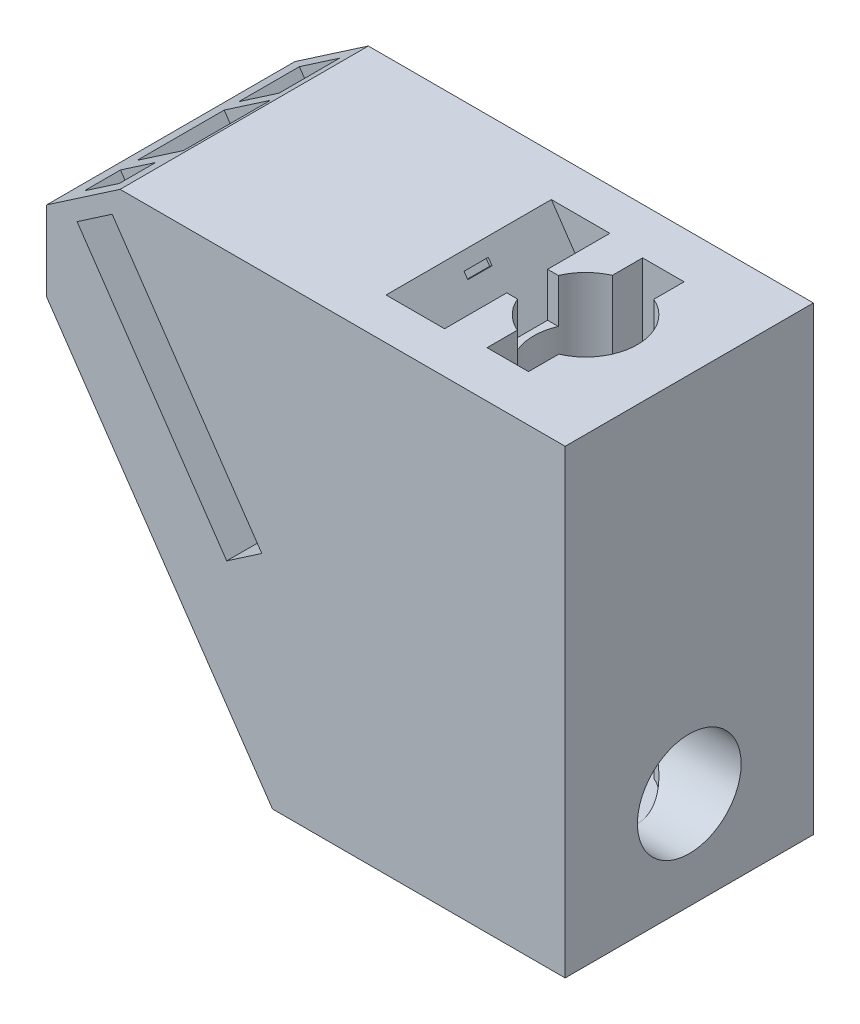
SolidWorks part; units mm, degrees
ref_plane "Front Plane" through (0, 0, 0) normal (0, 0, 1) x (1, 0, 0)
ref_plane "Top Plane" through (0, 0, 0) normal (0, 1, 0) x (1, 0, 0)
ref_plane "Right Plane" through (0, 0, 0) normal (1, 0, 0) x (0, 0, -1)
sketch "Sketch1" plane through (0, 0, 0) normal (0, 0, 1) x (1, 0, 0)
  line L6 (2.54, 23.749) -> (2.54, 14.224) construction
  line L7 (0, 0) -> (5.08, 0)
  line L8 (0, 0) -> (0, 14.224)
  line L9 (0, 14.224) -> (5.08, 14.224)
  line L14 (5.08, 0) -> (5.08, 14.224)
  line L19 (-4.6156, 24.384) -> (-4.0424, 23.5451)
  line L29 (-11.679, 6.821) -> (-21.27, 20.8572)
  line L31 (-22.86, -3.81) -> (8.89, -3.81)
  line L33 (-3.4692, 22.7063) -> (-1.0331, 19.1411)
  line L34 (-21.27, 20.8572) -> (-22.86, 19.7707)
  line L35 (-4.0424, 23.5451) -> (-3.4692, 22.7063)
  line L36 (-28.3165, 23.749) -> (25.4257, 23.749)
  line L37 (-28.3165, 23.749) -> (-28.3165, 38.989)
  line L38 (-28.3165, 38.989) -> (25.4257, 38.989)
  line L39 (25.4257, 23.749) -> (25.4257, 38.989)
  line L40 (2.54, 38.989) -> (2.54, 23.749) construction
  line L41 (2.54, 31.369) -> (-11.8891, 14.2184) construction
  line L42 (-21.27, 20.8572) -> (-17.9673, 23.1139)
  line L43 (-11.679, 6.821) -> (-8.3764, 9.0777)
  line L44 (-8.3764, 9.0777) -> (-9.5047, 10.729)
  line L45 (-1.0331, 19.1411) -> (0, 19.1411)
  line L46 (-17.9673, 23.1139) -> (-16.1085, 24.384)
  line L47 (-16.1085, 24.384) -> (-4.6156, 24.384)
  line L48 (0, 19.1411) -> (0, 14.224)
  line L49 (-4.329, 23.9646) -> (-17.443, 23.4721)
  line L50 (-4.329, 23.9646) -> (-3.7558, 23.1257)
  line L51 (-3.7558, 23.1257) -> (-8.3764, 9.0777)
  line L52 (-8.8063, 9.7068) -> (2.54, 42.6656) construction
  line L53 (2.54, 38.989) -> (2.54, 42.6656) construction
  line L54 (8.89, -3.81) -> (8.89, 24.384)
  line L55 (8.89, 24.384) -> (5.08, 24.384)
  line L56 (5.08, 14.224) -> (5.08, 24.384)
  line L57 (2.54, 23.749) -> (-4.0424, 23.5451) construction
  line L58 (2.54, 38.989) -> (-4.0424, 23.5451) construction
  line L59 (-4.0424, 23.5451) -> (-9.5047, 10.729) construction
  line L60 (-4.0424, 23.5451) -> (-17.9673, 23.1139) construction
  line L61 (-17.9673, 23.1139) -> (-9.5047, 10.729)
  line L62 (-8.8063, 9.7068) -> (-9.8549, 8.9903) construction
  line L63 (-9.8549, 8.9903) -> (-18.2379, 21.2588) construction
  line L64 (-18.2379, 21.2588) -> (-17.1893, 21.9753) construction
  line L69 (-17.1893, 21.9753) -> (2.54, 24.3311) construction
  line L70 (-22.86, 19.7707) -> (-22.86, -3.81)
  dimension "D1" = 5.08
  dimension "D2" = 14.224
  dimension "D3" = 0.635
  dimension "D4" = 10.16
  dimension "D5" = 4
  dimension "D6" = 15.24
  dimension "D7" = 17
  dimension "D8" = 31.75
  dimension "D9" = 1.59
  dimension "D10" = 1.016
  dimension "D11" = 6.35
  dimension "D12" = 3.81
  dimension "D13" = 3.81
  dimension "D14" = 0.635
  dimension "D15" = 0.508
  dimension "D16" = 0.508
  dimension "D17" = 0.762
  dimension "D18" = 14.859
  dimension "D19" = 1.27
  dimension "D20" = 15
extrude "Boss-Extrude1" add sketch "Sketch1" along normal blind 2.5 contours L34 L70 L31 L54 L36 L56 L14 L7 L8 L48 L45 L33 L35 L19 L46 L61 L44 L43 L29 | L47 L46 L36 L19 | L56 L36 L54 L55
sketch "Sketch2" plane through (0, 0, 2.5) normal (0, 0, 1) x (1, 0, 0)
  line L0 (-21.27, 20.8572) -> (-11.679, 6.821)
  line L1 (-21.27, 20.8572) -> (-18.0093, 23.0852)
  line L2 (-11.679, 6.821) -> (-8.4184, 9.049)
  line L3 (-18.0093, 23.0852) -> (-8.4184, 9.049)
  line L4 (-18.0093, 23.0852) -> (-16.1085, 24.384)
  line L5 (-16.1085, 24.384) -> (8.89, 24.384)
  line L6 (8.89, 24.384) -> (8.89, -3.81)
  line L7 (8.89, -3.81) -> (-22.86, -3.81)
  line L8 (-22.86, -3.81) -> (-22.86, 19.7707)
  line L9 (-22.86, 19.7707) -> (-21.27, 20.8572)
  line M1 (-21.27, 20.8572) -> (-22.86, 19.7707)
  line M2 (-22.86, 19.7707) -> (-22.86, -3.81)
  line M3 (-22.86, -3.81) -> (8.89, -3.81)
  line M4 (8.89, -3.81) -> (8.89, 24.384)
  line M5 (8.89, 24.384) -> (5.08, 24.384)
  line M6 (5.08, 24.384) -> (5.08, 0)
  line M7 (5.08, 0) -> (0, 0)
  line M8 (0, 0) -> (0, 19.1411)
  line M9 (0, 19.1411) -> (-1.0331, 19.1411)
  line M10 (-1.0331, 19.1411) -> (-3.7558, 23.1257)
  line M11 (-3.7558, 23.1257) -> (-8.3764, 9.0777)
  line M12 (-8.3764, 9.0777) -> (-11.679, 6.821)
  line M13 (-11.679, 6.821) -> (-21.27, 20.8572)
extrude "Boss-Extrude2" add sketch "Sketch2" along normal blind 6.35 contours M13 M1 M2 M3 M4 M5 M6 M7 M8 M9 M10 M11 M12 | L5 L4 L3 M12 M11 M10 M9 M8 M7 M6
sketch "Sketch3" plane through (0, 0, 0) normal (0, 0, -1) x (-1, 0, 0)
  line L0 (-8.89, 24.384) -> (-8.89, -3.81)
  line L1 (-8.89, -3.81) -> (22.86, -3.81)
  line L2 (22.86, -3.81) -> (22.86, 19.7707)
  line L3 (22.86, 19.7707) -> (21.27, 20.8572)
  line L4 (21.27, 20.8572) -> (11.679, 6.821)
  line L5 (11.679, 6.821) -> (8.3764, 9.0777)
  line L6 (8.3764, 9.0777) -> (18.0093, 23.0852)
  line L7 (18.0093, 23.0852) -> (16.1085, 24.384)
  line L8 (16.1085, 24.384) -> (-8.89, 24.384)
extrude "Boss-Extrude3" add sketch "Sketch3" along normal blind 6.35
sketch "Sketch4" plane through (0, 24.384, 0) normal (0, 1, 0) x (1, 0, 0)
  line L0 (2.54, 0) -> (2.54, -2.5) construction
  line L1 (-4.6156, 0) -> (5.08, 0) construction
  line L2 (5.08, -2.5) -> (-4.6156, -2.5) construction
  line L3 (-22.86, 0) -> (8.89, 0) construction
  line L4 (5.08, -2.5) -> (5.08, 0) construction
  circle A0 centre (2.54, -1.25) radius 3.175
  dimension "D2" = 6.35
  dimension "D1" = 2.54
extrude "Cut-Extrude1" cut sketch "Sketch4" against normal blind 25.4
sketch "Sketch5" plane through (0, -1.016, 0) normal (0, 1, 0) x (1, 0, 0)
  circle A0 centre (2.54, -1.25) radius 1.5875
  circle A1 centre (2.54, -1.25) radius 3.175
  circle A2 centre (2.54, -1.25) radius 3.175 construction
  dimension "D2" = 3.175
  dimension "D1" = 0
extrude "Cut-Extrude2" cut sketch "Sketch5" against normal blind 25.4
sketch "Sketch6" plane through (0, 0, 8.85) normal (0, 0, 1) x (1, 0, 0)
  line L0 (-22.86, 16.4309) -> (-9.0294, -3.81)
  line L1 (-22.86, 19.7707) -> (-22.86, -3.81) construction
  line L2 (-22.86, -3.81) -> (8.89, -3.81) construction
  line L3 (-11.679, 6.821) -> (-21.27, 20.8572) construction
  line L4 (-22.86, 16.4309) -> (-22.86, -3.81)
  line L5 (-22.86, -3.81) -> (-9.0294, -3.81)
  dimension "D1" = 3.81
extrude "Cut-Extrude3" cut sketch "Sketch6" against normal blind 25.4
sketch "Sketch7" plane through (8.89, 0, 0) normal (1, 0, 0) x (0, 0, -1)
  line L0 (1.925, -1.016) -> (-4.425, -1.016) construction
  line L1 (1.925, -1.016) -> (-4.425, -1.016)
  line L2 (-8.85, 2.159) -> (6.35, 2.159) construction
  line L3 (-8.85, -3.81) -> (-8.85, 24.384) construction
  line L4 (6.35, 24.384) -> (6.35, -3.81) construction
  circle A0 centre (-1.25, 2.159) radius 3.175
  dimension "D1" = 6.35
extrude "Cut-Extrude4" cut sketch "Sketch7" against normal up to next contours L2 A0 | A0 L2
sketch "Sketch8" plane through (0, 24.384, 0) normal (0, 1, 0) x (1, 0, 0)
  line L1 (1.27, -6.0125) -> (3.81, -6.0125)
  line L2 (1.27, -6.0125) -> (1.27, 3.5125)
  line L3 (1.27, 3.5125) -> (3.81, 3.5125)
  line L4 (3.81, -6.0125) -> (3.81, 3.5125)
  line L5 (1.27, -6.0125) -> (3.81, 3.5125) construction
  line L6 (1.27, 3.5125) -> (3.81, -6.0125) construction
  point P0 (2.54, -1.25)
  dimension "D1" = 9.525
  dimension "D2" = 2.54
extrude "Cut-Extrude5" cut sketch "Sketch8" against normal up to surface (25.4 mm away) up to face at (2.54, -1.016, 2.8375)
sketch "Sketch9" plane through (-6.8946, 10.0902, 0) normal (-0.5642, 0.8257, 0) x (0.8257, 0.5642, 0)
  line L1 (-1.8455, -4.6028) -> (-3.5726, -4.6028)
  line L2 (-3.5726, -4.6028) -> (-3.5726, -5.6188)
  line L3 (-3.5726, -5.6188) -> (-2.6836, -5.6188)
  line L4 (-2.6836, -5.6188) -> (-2.6836, -8.85)
  line L5 (-1.8455, -8.85) -> (-5.7946, -8.85) construction
  line L6 (-2.6836, -8.85) -> (-1.8455, -8.85)
  line L9 (-1.7946, 6.35) -> (-1.7946, 0) construction
  line L10 (-3.6235, 0.7312) -> (-3.6235, 1.6202)
  line L11 (-1.7946, 0.7312) -> (-3.6235, 0.7312)
  line L12 (-2.7091, 0.7312) -> (-2.7091, -4.6028) construction
  line L13 (-5.7946, 6.35) -> (-5.2866, 6.35)
  line L14 (-5.7946, 6.35) -> (-5.7946, -8.85)
  line L15 (-5.7946, -8.85) -> (-5.2866, -8.85)
  line L16 (-5.2866, 6.35) -> (-5.2866, -8.85)
  line L17 (-0.6688, -2.5) -> (-0.6688, 0) construction
  line L18 (-1.8455, -8.85) -> (-1.8455, -2.5) construction
  line L19 (-3.6235, 1.6202) -> (-2.3026, 1.6202)
  line L20 (-2.3026, 1.6202) -> (-2.3026, 6.35)
  line L21 (-5.7946, 6.35) -> (-1.7946, 6.35) construction
  line L23 (-1.7946, -2.5) -> (-1.7946, 0) construction
  line L24 (-1.7946, 0.7312) -> (-1.7946, 6.35)
  line L27 (-1.8455, 6.35) -> (0.4567, 6.35) construction
  line L28 (-2.3026, 6.35) -> (-1.7946, 6.35)
  point P28 (-0.6688, -1.25)
  line M15 (-1.7946, 0) -> (-1.7946, 6.35)
  line M16 (-1.7946, 6.35) -> (-5.7946, 6.35)
  line M17 (-5.7946, 6.35) -> (-5.7946, -8.85)
  line M18 (-5.7946, -8.85) -> (-1.8455, -8.85)
  line M19 (-1.8455, -8.85) -> (-1.8455, -2.5)
  dimension "D1" = 0.508
  dimension "D2" = 5.334
  dimension "D3" = 1.9812
  dimension "D4" = 0.508
  dimension "D5" = 0.889
  dimension "D6" = 0.889
  dimension "D7" = 1.016
  dimension "D8" = 1.778
extrude "Boss-Extrude4" add sketch "Sketch9" along normal up to surface (17 mm away) contours L16 M16 M17 M18 | L20 L19 L10 L11 M15 M16 | L3 L4 L1 L2 M18 M19 up to face at (-17.2912, 23.5758, 1.25)
sketch "Sketch10" plane through (-6.8946, 10.0902, 0) normal (-0.5642, 0.8257, 0) x (0.8257, 0.5642, 0)
  line L15 (-5.2866, -8.85) -> (-2.6836, -8.85)
  line L16 (-2.6836, -8.85) -> (-2.6836, -5.6188)
  line L17 (-2.6836, -5.6188) -> (-3.5726, -5.6188)
  line L18 (-3.5726, -5.6188) -> (-3.5726, -4.6028)
  line L19 (-3.5726, -4.6028) -> (-1.8455, -4.6028)
  line L20 (-1.8455, -4.6028) -> (-1.8455, -2.5)
  line L21 (-1.8455, -2.5) -> (-1.7946, -2.5)
  line L22 (-1.7946, -2.5) -> (-1.7946, 0)
  line L23 (-1.7946, 0) -> (-1.7946, 0.7312)
  line L24 (-1.7946, 0.7312) -> (-3.6235, 0.7312)
  line L25 (-3.6235, 0.7312) -> (-3.6235, 1.6202)
  line L26 (-3.6235, 1.6202) -> (-2.3026, 1.6202)
  line L27 (-2.3026, 1.6202) -> (-2.3026, 6.35)
  line L28 (-2.3026, 6.35) -> (-5.2866, 6.35)
  line L29 (-5.2866, 6.35) -> (-5.2866, -8.85)
  line L30 (-5.2866, -8.85) -> (-2.6836, -8.85)
  line L31 (-2.6836, -8.85) -> (-2.6836, -5.6188)
  line L32 (-2.6836, -5.6188) -> (-3.5726, -5.6188)
  line L33 (-3.5726, -5.6188) -> (-3.5726, -4.6028)
  line L34 (-3.5726, -4.6028) -> (-1.8455, -4.6028)
  line L35 (-1.8455, -4.6028) -> (-1.8455, -2.5)
  line L36 (-1.8455, -2.5) -> (-1.7946, -2.5)
  line L37 (-1.7946, -2.5) -> (-1.7946, 0)
  line L38 (-1.7946, 0) -> (-1.7946, 0.7312)
  line L39 (-1.7946, 0.7312) -> (-3.6235, 0.7312)
  line L40 (-3.6235, 0.7312) -> (-3.6235, 1.6202)
  line L41 (-3.6235, 1.6202) -> (-2.3026, 1.6202)
  line L42 (-2.3026, 1.6202) -> (-2.3026, 6.35)
  line L43 (-2.3026, 6.35) -> (-5.2866, 6.35)
  line L44 (-5.2866, 6.35) -> (-5.2866, -8.85)
  dimension "D1" = 0
extrude "Boss-Extrude5" add sketch "Sketch10" along normal blind 1.016
sketch "Sketch11" plane through (-16.4856, 24.1263, 0) normal (-0.5642, 0.8257, 0) x (0.8257, 0.5642, 0)
  line L0 (-7.7204, -8.85) -> (-5.2866, -8.85) construction
  line L1 (-5.2866, -8.85) -> (-5.2866, 6.35) construction
  line L2 (-5.2866, 6.35) -> (-7.7204, 6.35) construction
  line L3 (-7.7204, 6.35) -> (-7.7204, -8.85) construction
  line L4 (-3.6235, 0.7312) -> (-1.8455, 0.7312) construction
  line L5 (-1.8455, 0.7312) -> (-1.8455, 0) construction
  line L6 (-1.8455, 0) -> (-0.6688, 0) construction
  line L7 (-0.6688, 0) -> (-0.6688, -2.5) construction
  line L8 (-0.6688, -2.5) -> (-1.8455, -2.5) construction
  line L9 (-1.8455, -2.5) -> (-1.8455, -4.6028) construction
  line L10 (-1.8455, -4.6028) -> (-3.5726, -4.6028) construction
  line L11 (-3.5726, -4.6028) -> (-3.5726, -5.6188) construction
  line L12 (-3.5726, -5.6188) -> (-2.6836, -5.6188) construction
  line L13 (-2.6836, -5.6188) -> (-2.6836, -8.85) construction
  line L14 (-2.6836, -8.85) -> (0.4567, -8.85) construction
  line L15 (0.4567, -8.85) -> (0.4567, 6.35) construction
  line L16 (0.4567, 6.35) -> (-2.3026, 6.35) construction
  line L17 (-2.3026, 6.35) -> (-2.3026, 1.6202) construction
  line L18 (-2.3026, 1.6202) -> (-3.6235, 1.6202) construction
  line L19 (-3.6235, 1.6202) -> (-3.6235, 0.7312) construction
  line L20 (-7.7204, -8.85) -> (-5.2866, -8.85)
  line L21 (-5.2866, -8.85) -> (-5.2866, 6.35)
  line L22 (-5.2866, 6.35) -> (-7.7204, 6.35)
  line L23 (-7.7204, 6.35) -> (-7.7204, -8.85)
  line L24 (-3.6235, 0.7312) -> (-1.8455, 0.7312)
  line L25 (-1.8455, 0.7312) -> (-1.8455, 0)
  line L26 (-1.8455, 0) -> (-0.6688, 0)
  line L27 (-0.6688, 0) -> (-0.6688, -2.5)
  line L28 (-0.6688, -2.5) -> (-1.8455, -2.5)
  line L29 (-1.8455, -2.5) -> (-1.8455, -4.6028)
  line L30 (-1.8455, -4.6028) -> (-3.5726, -4.6028)
  line L31 (-3.5726, -4.6028) -> (-3.5726, -5.6188)
  line L32 (-3.5726, -5.6188) -> (-2.6836, -5.6188)
  line L33 (-2.6836, -5.6188) -> (-2.6836, -8.85)
  line L34 (-2.6836, -8.85) -> (0.4567, -8.85)
  line L35 (0.4567, -8.85) -> (0.4567, 6.35)
  line L36 (0.4567, 6.35) -> (-2.3026, 6.35)
  line L37 (-2.3026, 6.35) -> (-2.3026, 1.6202)
  line L38 (-2.3026, 1.6202) -> (-3.6235, 1.6202)
  line L39 (-3.6235, 1.6202) -> (-3.6235, 0.7312)
  line L41 (-1.8455, 0) -> (-0.6688, 0)
  line L42 (-1.8455, 0) -> (-1.8455, -2.5)
  line L43 (-1.8455, -2.5) -> (-0.6688, -2.5)
  line L44 (-0.6688, 0) -> (-0.6688, -2.5)
  line M25 (-3.6235, 0.7312) -> (-1.8455, 0.7312)
  line M26 (-1.8455, 0.7312) -> (-1.8455, 0)
  line M27 (-1.8455, 0) -> (-0.6688, 0)
  line M28 (-0.6688, 0) -> (-0.6688, -2.5)
  line M29 (-0.6688, -2.5) -> (-1.8455, -2.5)
  line M30 (-1.8455, -2.5) -> (-1.8455, -4.6028)
  line M31 (-1.8455, -4.6028) -> (-3.5726, -4.6028)
  line M32 (-3.5726, -4.6028) -> (-3.5726, -5.6188)
  line M33 (-3.5726, -5.6188) -> (-2.6836, -5.6188)
  line M34 (-2.6836, -5.6188) -> (-2.6836, -8.85)
  line M35 (-2.6836, -8.85) -> (0.4567, -8.85)
  line M36 (0.4567, -8.85) -> (0.4567, 6.35)
  line M37 (0.4567, 6.35) -> (-2.3026, 6.35)
  line M38 (-2.3026, 6.35) -> (-2.3026, 1.6202)
  line M39 (-2.3026, 1.6202) -> (-3.6235, 1.6202)
  line M40 (-3.6235, 1.6202) -> (-3.6235, 0.7312)
extrude "Boss-Extrude6" add sketch "Sketch11" along normal blind 1.27 contours L42 M27 M29 M28 | M40 M25 M26 M27 M28 M29 M30 M31 M32 M33 M34 M35 M36 M37 M38 M39 | L22 L23 L20 L21
sketch "Sketch12" plane through (0, 0, 8.85) normal (0, 0, 1) x (1, 0, 0)
  line L0 (-16.1085, 24.384) -> (-18.3596, 24.384)
  line L1 (-19.4178, 23.6609) -> (-16.825, 25.4326) construction
  line L2 (-18.3596, 24.384) -> (-16.825, 25.4326)
  line L3 (-16.825, 25.4326) -> (-16.1085, 24.384)
  line L4 (-22.86, 19.7707) -> (-22.86, 21.3089)
  line L5 (-23.5765, 20.8193) -> (-21.567, 22.1923) construction
  line L6 (-22.86, 21.3089) -> (-23.5765, 20.8193)
  line L7 (-23.5765, 20.8193) -> (-22.86, 19.7707)
extrude "Cut-Extrude6" cut sketch "Sketch12" against normal through all
sketch "Sketch13" plane through (0, 19.1411, 0) normal (0, 1, 0) x (1, 0, 0)
  line L3 (-0.3786, 0) -> (-1.0331, 0)
  line L4 (-1.0331, 0) -> (-1.0331, -2.5)
  line L5 (-1.0331, -2.5) -> (-0.3786, -2.5)
  line L6 (-0.3786, 0) -> (-1.0331, 0)
  line L7 (-1.0331, 0) -> (-1.0331, -2.5)
  line L8 (-1.0331, -2.5) -> (-0.3786, -2.5)
  arc A1 (-0.3786, 0) -> (-0.3786, -2.5) centre (2.54, -1.25) ccw
  arc A2 (-0.3786, 0) -> (-0.3786, -2.5) centre (2.54, -1.25) ccw
  dimension "D1" = 0
extrude "Boss-Extrude7" add sketch "Sketch13" along normal blind 2.54
sketch "Sketch14" plane through (8.2119, 5.6112, 0) normal (0.8257, 0.5642, 0) x (0, 0, -1)
  line L0 (0, 22.2288) -> (0, 22.7368) construction
  line L1 (0, 22.7368) -> (-2.5, 22.7368) construction
  line L2 (-2.5, 22.7368) -> (-2.5, 22.2288) construction
  line L3 (-2.5, 22.2288) -> (0, 22.2288) construction
  line L4 (0, 16.3868) -> (0, 21.2128) construction
  line L5 (0, 21.2128) -> (-2.5, 21.2128) construction
  line L6 (-2.5, 21.2128) -> (-2.5, 16.3868) construction
  line L7 (-2.5, 16.3868) -> (0, 16.3868) construction
  line L8 (0, 22.2288) -> (0, 22.7368)
  line L9 (0, 22.7368) -> (-2.5, 22.7368)
  line L10 (-2.5, 22.7368) -> (-2.5, 22.2288)
  line L11 (-2.5, 22.2288) -> (0, 22.2288)
  line L12 (0, 16.3868) -> (0, 21.2128)
  line L13 (0, 21.2128) -> (-2.5, 21.2128)
  line L14 (-2.5, 21.2128) -> (-2.5, 16.3868)
  line L15 (-2.5, 16.3868) -> (0, 16.3868)
  dimension "D1" = 2.5
sketch "Sketch15" plane through (0, 0, 0) normal (0, 0, 1) x (1, 0, 0)
  line L0 (-4.329, 23.9646) -> (-3.7558, 23.1257)
  line L1 (-4.329, 23.9646) -> (-4.6156, 24.384) construction
  line L2 (-3.7558, 23.1257) -> (-1.0331, 19.1411) construction
  line L3 (-4.0745, 23.277) -> (-3.9277, 23.3774)
  line L4 (-4.3038, 23.6126) -> (-4.5389, 23.9567)
  line L5 (-4.5389, 23.9567) -> (-4.329, 23.9646)
  line L6 (-4.3038, 23.6126) -> (-4.157, 23.7129)
  line L7 (-4.0745, 23.277) -> (-3.8257, 22.913)
  line L8 (-3.8257, 22.913) -> (-3.7558, 23.1257)
  line L9 (-4.0424, 23.5451) -> (-3.9209, 23.3673) construction
  line L10 (-4.0424, 23.5451) -> (-4.1638, 23.7229) construction
  line L11 (-1.0331, 19.1411) -> (-3.7558, 23.1257) construction
  line L25 (-1.0331, 19.1411) -> (-1.0331, 21.6811)
  line L26 (-1.0331, 21.6811) -> (-0.3786, 21.6811)
  line L27 (-0.3786, 21.6811) -> (-0.3786, 24.384)
  line L28 (-0.3786, 24.384) -> (-4.6156, 24.384)
  line L29 (-4.6156, 24.384) -> (-4.329, 23.9646)
  line L30 (-4.329, 23.9646) -> (-10.0694, 23.749)
  line L31 (-10.0694, 23.749) -> (-17.0378, 23.749)
  line L32 (-17.0378, 23.749) -> (-18.0093, 23.0852)
  line L33 (-18.0093, 23.0852) -> (-8.9521, 9.9148)
  line L34 (-8.9521, 9.9148) -> (-8.9496, 9.9166)
  line L35 (-8.9496, 9.9166) -> (-8.3764, 9.0777)
  line L36 (-8.3764, 9.0777) -> (-3.7558, 23.1257)
  line L37 (-3.7558, 23.1257) -> (-1.0331, 19.1411)
  line L38 (-1.0331, 19.1411) -> (-1.0331, 21.6811)
  line L39 (-1.0331, 21.6811) -> (-0.3786, 21.6811)
  line L40 (-0.3786, 21.6811) -> (-0.3786, 24.384)
  line L41 (-0.3786, 24.384) -> (-4.6156, 24.384)
  line L42 (-4.6156, 24.384) -> (-4.329, 23.9646)
  line L43 (-4.329, 23.9646) -> (-10.0694, 23.749)
  line L44 (-10.0694, 23.749) -> (-17.0378, 23.749)
  line L45 (-17.0378, 23.749) -> (-18.0093, 23.0852)
  line L46 (-18.0093, 23.0852) -> (-8.9521, 9.9148)
  line L47 (-8.9521, 9.9148) -> (-8.9496, 9.9166)
  line L48 (-8.9496, 9.9166) -> (-8.3764, 9.0777)
  line L49 (-8.3764, 9.0777) -> (-3.7558, 23.1257)
  line L50 (-3.7558, 23.1257) -> (-1.0331, 19.1411)
  line M26 (-4.329, 23.9646) -> (-10.0694, 23.749)
  line M32 (-8.3764, 9.0777) -> (-3.7558, 23.1257)
  dimension "D1" = 0.4064
  dimension "D2" = 0.1778
  dimension "D3" = 0
  dimension "D4" = 0.2032
extrude "Boss-Extrude8" add sketch "Sketch15" along normal blind 2.54 contours L4 L6 L0 M26 | L3 L7 L0 M32
sketch "Sketch16" plane through (0, 0, 0) normal (0, 0, 1) x (1, 0, 0)
  line L0 (-4.157, 23.7129) -> (-3.9277, 23.3774)
  line L1 (-4.0745, 23.277) -> (-3.9277, 23.3774)
  line L2 (-4.0745, 23.277) -> (-4.3038, 23.6126)
  line L3 (-4.3038, 23.6126) -> (-4.157, 23.7129)
  line L17 (-3.8257, 22.913) -> (-4.0745, 23.277)
  line L18 (-4.0745, 23.277) -> (-3.9277, 23.3774)
  line L19 (-3.9277, 23.3774) -> (-1.0331, 19.1411)
  line L20 (-1.0331, 19.1411) -> (-1.0331, 21.6811)
  line L21 (-1.0331, 21.6811) -> (-0.3786, 21.6811)
  line L22 (-0.3786, 21.6811) -> (-0.3786, 24.384)
  line L23 (-0.3786, 24.384) -> (-4.6156, 24.384)
  line L24 (-4.6156, 24.384) -> (-4.157, 23.7129)
  line L25 (-4.157, 23.7129) -> (-4.3038, 23.6126)
  line L26 (-4.3038, 23.6126) -> (-4.5389, 23.9567)
  line L27 (-4.5389, 23.9567) -> (-10.0694, 23.749)
  line L28 (-10.0694, 23.749) -> (-17.0378, 23.749)
  line L29 (-17.0378, 23.749) -> (-18.0093, 23.0852)
  line L30 (-18.0093, 23.0852) -> (-8.9521, 9.9148)
  line L31 (-8.9521, 9.9148) -> (-8.9496, 9.9166)
  line L32 (-8.9496, 9.9166) -> (-8.3764, 9.0777)
  line L33 (-8.3764, 9.0777) -> (-3.8257, 22.913)
  line L34 (-3.8257, 22.913) -> (-4.0745, 23.277)
  line L35 (-4.0745, 23.277) -> (-3.9277, 23.3774)
  line L36 (-3.9277, 23.3774) -> (-1.0331, 19.1411)
  line L37 (-1.0331, 19.1411) -> (-1.0331, 21.6811)
  line L38 (-1.0331, 21.6811) -> (-0.3786, 21.6811)
  line L39 (-0.3786, 21.6811) -> (-0.3786, 24.384)
  line L40 (-0.3786, 24.384) -> (-4.6156, 24.384)
  line L41 (-4.6156, 24.384) -> (-4.157, 23.7129)
  line L42 (-4.157, 23.7129) -> (-4.3038, 23.6126)
  line L43 (-4.3038, 23.6126) -> (-4.5389, 23.9567)
  line L44 (-4.5389, 23.9567) -> (-10.0694, 23.749)
  line L45 (-10.0694, 23.749) -> (-17.0378, 23.749)
  line L46 (-17.0378, 23.749) -> (-18.0093, 23.0852)
  line L47 (-18.0093, 23.0852) -> (-8.9521, 9.9148)
  line L48 (-8.9521, 9.9148) -> (-8.9496, 9.9166)
  line L49 (-8.9496, 9.9166) -> (-8.3764, 9.0777)
  line L50 (-8.3764, 9.0777) -> (-3.8257, 22.913)
  line M19 (-4.0745, 23.277) -> (-3.9277, 23.3774)
  line M26 (-4.157, 23.7129) -> (-4.3038, 23.6126)
  dimension "D1" = 0
extrude "Boss-Extrude9" add sketch "Sketch16" along normal blind 0.508 contours L2 L0 M19 M26
sketch "Sketch17" plane through (0, 0, 2.5) normal (0, 0, -1) x (-1, 0, 0)
  line L0 (4.157, 23.7129) -> (3.9277, 23.3774)
  line L1 (3.9277, 23.3774) -> (4.0745, 23.277)
  line L2 (4.0745, 23.277) -> (4.3038, 23.6126)
  line L3 (4.3038, 23.6126) -> (4.157, 23.7129)
  line L17 (4.0745, 23.277) -> (3.8257, 22.913)
  line L18 (3.8257, 22.913) -> (8.3764, 9.0777)
  line L19 (8.3764, 9.0777) -> (8.9496, 9.9166)
  line L20 (8.9496, 9.9166) -> (8.9916, 9.8879)
  line L21 (8.9916, 9.8879) -> (18.0093, 23.0852)
  line L22 (18.0093, 23.0852) -> (17.0378, 23.749)
  line L23 (17.0378, 23.749) -> (10.0694, 23.749)
  line L24 (10.0694, 23.749) -> (4.5389, 23.9567)
  line L25 (4.5389, 23.9567) -> (4.3038, 23.6126)
  line L26 (4.3038, 23.6126) -> (4.157, 23.7129)
  line L27 (4.157, 23.7129) -> (4.6156, 24.384)
  line L28 (4.6156, 24.384) -> (0.3786, 24.384)
  line L29 (0.3786, 24.384) -> (0.3786, 21.6811)
  line L30 (0.3786, 21.6811) -> (1.0331, 21.6811)
  line L31 (1.0331, 21.6811) -> (1.0331, 19.1411)
  line L32 (1.0331, 19.1411) -> (3.9277, 23.3774)
  line L33 (3.9277, 23.3774) -> (4.0745, 23.277)
  line L34 (4.0745, 23.277) -> (3.8257, 22.913)
  line L35 (3.8257, 22.913) -> (8.3764, 9.0777)
  line L36 (8.3764, 9.0777) -> (8.9496, 9.9166)
  line L37 (8.9496, 9.9166) -> (8.9916, 9.8879)
  line L38 (8.9916, 9.8879) -> (18.0093, 23.0852)
  line L39 (18.0093, 23.0852) -> (17.0378, 23.749)
  line L40 (17.0378, 23.749) -> (10.0694, 23.749)
  line L41 (10.0694, 23.749) -> (4.5389, 23.9567)
  line L42 (4.5389, 23.9567) -> (4.3038, 23.6126)
  line L43 (4.3038, 23.6126) -> (4.157, 23.7129)
  line L44 (4.157, 23.7129) -> (4.6156, 24.384)
  line L45 (4.6156, 24.384) -> (0.3786, 24.384)
  line L46 (0.3786, 24.384) -> (0.3786, 21.6811)
  line L47 (0.3786, 21.6811) -> (1.0331, 21.6811)
  line L48 (1.0331, 21.6811) -> (1.0331, 19.1411)
  line L49 (1.0331, 19.1411) -> (3.9277, 23.3774)
  line L50 (3.9277, 23.3774) -> (4.0745, 23.277)
  line M27 (4.3038, 23.6126) -> (4.157, 23.7129)
  line M34 (3.9277, 23.3774) -> (4.0745, 23.277)
  dimension "D1" = 0
extrude "Boss-Extrude10" add sketch "Sketch17" along normal blind 0.508 contours L2 L0 M34 M27
sketch "Sketch18" plane through (0, 0, 2.5) normal (0, 0, -1) x (-1, 0, 0)
  line L0 (1.0331, 21.6811) -> (1.0331, 24.384)
  line L5 (1.0331, 19.1411) -> (4.6156, 24.384)
  line L6 (4.6156, 24.384) -> (0.3786, 24.384)
  line L7 (0.3786, 24.384) -> (0.3786, 21.6811)
  line L8 (0.3786, 21.6811) -> (1.0331, 21.6811)
  line L9 (1.0331, 21.6811) -> (1.0331, 19.1411)
  line L10 (1.0331, 19.1411) -> (4.6156, 24.384)
  line L11 (4.6156, 24.384) -> (0.3786, 24.384)
  line L12 (0.3786, 24.384) -> (0.3786, 21.6811)
  line L13 (0.3786, 21.6811) -> (1.0331, 21.6811)
  line L14 (1.0331, 21.6811) -> (1.0331, 19.1411)
  line M6 (1.0331, 19.1411) -> (4.6156, 24.384)
  line M7 (4.6156, 24.384) -> (0.3786, 24.384)
  line M10 (1.0331, 21.6811) -> (1.0331, 19.1411)
  dimension "D1" = 0
extrude "Cut-Extrude7" cut sketch "Sketch18" against normal blind 3.81 contours L0 M10 M6 M7
sketch "Sketch19" plane through (0, 0, 0) normal (0, 0, 1) x (1, 0, 0)
  line L0 (-1.0331, 21.6811) -> (-1.0331, 24.384)
  line L5 (-0.3786, 24.384) -> (-4.6156, 24.384)
  line L6 (-4.6156, 24.384) -> (-1.0331, 19.1411)
  line L7 (-1.0331, 19.1411) -> (-1.0331, 21.6811)
  line L8 (-1.0331, 21.6811) -> (-0.3786, 21.6811)
  line L9 (-0.3786, 21.6811) -> (-0.3786, 24.384)
  line L10 (-0.3786, 24.384) -> (-4.6156, 24.384)
  line L11 (-4.6156, 24.384) -> (-1.0331, 19.1411)
  line L12 (-1.0331, 19.1411) -> (-1.0331, 21.6811)
  line L13 (-1.0331, 21.6811) -> (-0.3786, 21.6811)
  line L14 (-0.3786, 21.6811) -> (-0.3786, 24.384)
  line M6 (-0.3786, 24.384) -> (-4.6156, 24.384)
  line M7 (-4.6156, 24.384) -> (-1.0331, 19.1411)
  line M8 (-1.0331, 19.1411) -> (-1.0331, 21.6811)
  dimension "D1" = 0
extrude "Cut-Extrude8" cut sketch "Sketch19" against normal blind 3.81 contours L0 M8 M6 M7
sketch "Sketch20" plane through (0, 0, 0) normal (0, 0, 1) x (1, 0, 0)
  line L0 (-4.3038, 23.6126) -> (-10.0694, 23.749)
  line L8 (-8.3764, 9.0777) -> (-3.8257, 22.913)
  line L9 (-3.8257, 22.913) -> (-4.5389, 23.9567)
  line L10 (-4.5389, 23.9567) -> (-10.0694, 23.749)
  line L11 (-10.0694, 23.749) -> (-17.0378, 23.749)
  line L12 (-17.0378, 23.749) -> (-18.0093, 23.0852)
  line L13 (-18.0093, 23.0852) -> (-8.9521, 9.9148)
  line L14 (-8.9521, 9.9148) -> (-8.9496, 9.9166)
  line L15 (-8.9496, 9.9166) -> (-8.3764, 9.0777)
  line L16 (-8.3764, 9.0777) -> (-3.8257, 22.913)
  line L17 (-3.8257, 22.913) -> (-4.5389, 23.9567)
  line L18 (-4.5389, 23.9567) -> (-10.0694, 23.749)
  line L19 (-10.0694, 23.749) -> (-17.0378, 23.749)
  line L20 (-17.0378, 23.749) -> (-18.0093, 23.0852)
  line L21 (-18.0093, 23.0852) -> (-8.9521, 9.9148)
  line L22 (-8.9521, 9.9148) -> (-8.9496, 9.9166)
  line L23 (-8.9496, 9.9166) -> (-8.3764, 9.0777)
  point P6 (-10.0299, 23.749)
  line M10 (-3.8257, 22.913) -> (-4.5389, 23.9567)
  line M11 (-4.5389, 23.9567) -> (-10.0694, 23.749)
  dimension "D1" = 0
extrude "Boss-Extrude11" add sketch "Sketch20" along normal blind 3.81 contours L0 M10 M11
sketch "Sketch21" plane through (-4.365, -2.9826, 0) normal (0.8257, 0.5642, 0) x (0, 0, -1)
  line L0 (-4.6028, 30.4908) -> (-4.6028, 13.2368) construction
  line L1 (6.35, 30.4908) -> (5.334, 30.4908)
  line L2 (6.35, 30.4908) -> (6.35, 29.4748)
  line L3 (6.35, 29.4748) -> (5.334, 29.4748)
  line L4 (5.334, 30.4908) -> (5.334, 29.4748)
  line L5 (-4.6028, 13.2368) -> (-5.6188, 13.2368) construction
  line L6 (-5.6188, 13.2368) -> (-5.6188, 30.4908) construction
  line L7 (-5.6188, 30.4908) -> (-4.6028, 30.4908) construction
  line L8 (1.6202, 13.2368) -> (0.7312, 13.2368) construction
  line L9 (0.7312, 13.2368) -> (0.7312, 30.4908) construction
  line L10 (0.7312, 30.4908) -> (1.6202, 30.4908) construction
  line L11 (1.6202, 30.4908) -> (1.6202, 13.2368) construction
  line L12 (-4.6028, 30.4908) -> (-4.6028, 13.2368)
  line L13 (-4.6028, 13.2368) -> (-5.6188, 13.2368)
  line L14 (-5.6188, 13.2368) -> (-5.6188, 30.4908)
  line L15 (-5.6188, 30.4908) -> (-4.6028, 30.4908)
  line L16 (1.6202, 13.2368) -> (0.7312, 13.2368)
  line L17 (0.7312, 13.2368) -> (0.7312, 30.4908)
  line L18 (0.7312, 30.4908) -> (1.6202, 30.4908)
  line L19 (1.6202, 30.4908) -> (1.6202, 13.2368)
  line L20 (1.6202, 29.4748) -> (0.7312, 29.4748)
  line L21 (-4.6028, 29.4748) -> (-5.6188, 29.4748)
  line L23 (-8.85, 30.4908) -> (-7.834, 30.4908)
  line L24 (-8.85, 30.4908) -> (-8.85, 29.4748)
  line L25 (-8.85, 29.4748) -> (-7.834, 29.4748)
  line L26 (-7.834, 30.4908) -> (-7.834, 29.4748)
  point P21 (-5.6188, 29.2372)
  line M20 (6.35, 13.2368) -> (6.35, 30.4908)
  line M21 (6.35, 30.4908) -> (-8.85, 30.4908)
  line M22 (-8.85, 30.4908) -> (-8.85, 13.2368)
  dimension "D1" = 1.016
  dimension "D2" = 1.016
extrude "Boss-Extrude12" add sketch "Sketch21" along normal blind 3.302 contours L4 L3 M21 M20 | L20 L19 L17 M21 | L21 L12 L14 M21 | L26 L25 M21 M22
sketch "Sketch22" plane through (0, 0, 0) normal (0, 0, 1) x (1, 0, 0)
  line L0 (-4.0745, 23.277) -> (-4.2225, 21.7065)
  line L8 (-3.8257, 22.913) -> (-4.3038, 23.6126)
  line L9 (-4.3038, 23.6126) -> (-10.0694, 23.749)
  line L10 (-10.0694, 23.749) -> (-17.0378, 23.749)
  line L11 (-17.0378, 23.749) -> (-18.0093, 23.0852)
  line L12 (-18.0093, 23.0852) -> (-8.9521, 9.9148)
  line L13 (-8.9521, 9.9148) -> (-8.9496, 9.9166)
  line L14 (-8.9496, 9.9166) -> (-8.3764, 9.0777)
  line L15 (-8.3764, 9.0777) -> (-3.8257, 22.913)
  line L16 (-3.8257, 22.913) -> (-4.3038, 23.6126)
  line L17 (-4.3038, 23.6126) -> (-10.0694, 23.749)
  line L18 (-10.0694, 23.749) -> (-17.0378, 23.749)
  line L19 (-17.0378, 23.749) -> (-18.0093, 23.0852)
  line L20 (-18.0093, 23.0852) -> (-8.9521, 9.9148)
  line L21 (-8.9521, 9.9148) -> (-8.9496, 9.9166)
  line L22 (-8.9496, 9.9166) -> (-8.3764, 9.0777)
  line L23 (-8.3764, 9.0777) -> (-3.8257, 22.913)
  line M9 (-3.8257, 22.913) -> (-4.3038, 23.6126)
  line M16 (-8.3764, 9.0777) -> (-3.8257, 22.913)
  dimension "D2" = 1.27
  dimension "D1" = 0
extrude "Boss-Extrude13" add sketch "Sketch22" along normal blind 3.81 contours L0 M9 M16
